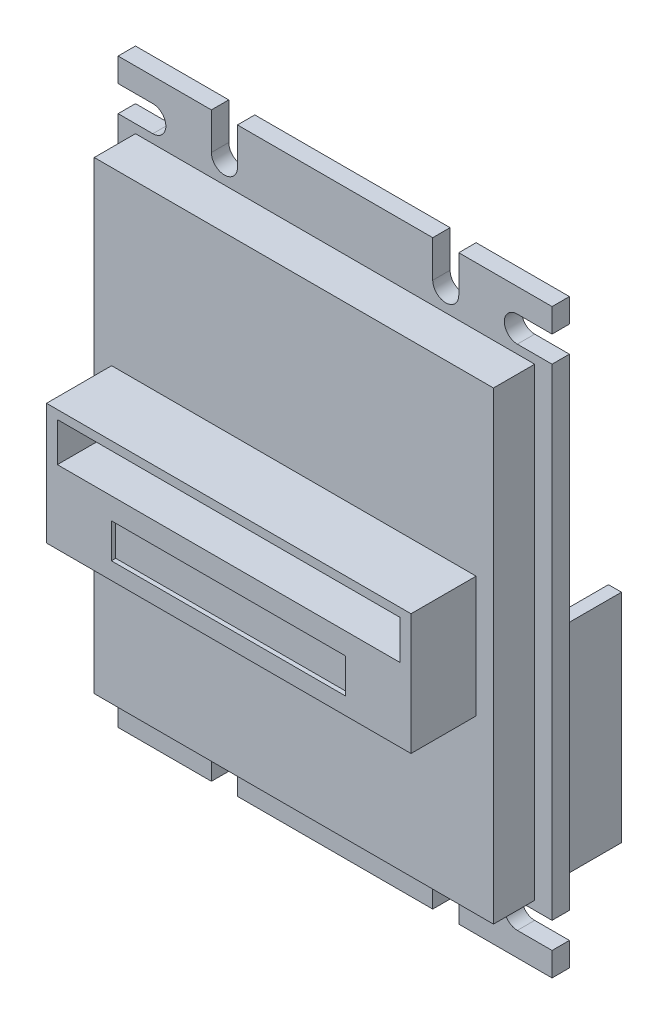
SolidWorks part; units mm, degrees
ref_plane "Front Plane" through (0, 0, 0) normal (0, 0, 1) x (1, 0, 0)
ref_plane "Top Plane" through (0, 0, 0) normal (0, 1, 0) x (1, 0, 0)
ref_plane "Right Plane" through (0, 0, 0) normal (1, 0, 0) x (0, 0, -1)
sketch "Sketch1" plane through (0, 0, 0) normal (0, 0, 1) x (1, 0, 0)
  line L0 (25.5, 0) -> (-25.5, 0) construction
  line L5 (-25.5, 67) -> (-25.5, -67) construction
  line L6 (25.5, 67) -> (25.5, -67) construction
  line L7 (0, -58.5) -> (0, 58.5) construction
  line L8 (25.5, 58.5) -> (-25.5, 58.5) construction
  line L9 (25.5, -58.5) -> (-25.5, -58.5) construction
  line L10 (25.5, 58.5) -> (50, 58.5) construction
  line L11 (-25.5, 58.5) -> (-50, 58.5) construction
  line L12 (50, -58.5) -> (25.5, -58.5) construction
  line L13 (-25.5, -58.5) -> (-50, -58.5) construction
  line L14 (22.5, 58.5) -> (22.5, 67)
  line L15 (28.5, 58.5) -> (28.5, 67)
  line L16 (-28.5, 58.5) -> (-28.5, 67)
  line L17 (-22.5, 58.5) -> (-22.5, 67)
  line L18 (22.5, -58.5) -> (22.5, -67)
  line L19 (28.5, -58.5) -> (28.5, -67)
  line L20 (-28.5, -58.5) -> (-28.5, -67)
  line L21 (-22.5, -58.5) -> (-22.5, -67)
  line L22 (-42, 27.0148) -> (42, 27.0148) construction
  line L23 (-42, 67) -> (-42, -67) construction
  line L24 (42, 67) -> (42, -67) construction
  line L25 (-42, 61.5) -> (-50, 61.5)
  line L26 (-42, 55.5) -> (-50, 55.5)
  line L27 (42, 61.5) -> (50, 61.5)
  line L28 (42, 55.5) -> (50, 55.5)
  line L29 (-42, -55.5) -> (-50, -55.5)
  line L30 (-42, -61.5) -> (-50, -61.5)
  line L31 (42, -55.5) -> (50, -55.5)
  line L32 (42, -61.5) -> (50, -61.5)
  line L33 (-50, 67) -> (-28.5, 67)
  line L34 (-22.5, 67) -> (22.5, 67)
  line L35 (28.5, 67) -> (50, 67)
  line L36 (-50, -67) -> (-28.5, -67)
  line L37 (-22.5, -67) -> (22.5, -67)
  line L38 (28.5, -67) -> (50, -67)
  line L39 (-50, 67) -> (-50, 61.5)
  line L40 (-50, 55.5) -> (-50, -55.5)
  line L41 (-50, -61.5) -> (-50, -67)
  line L42 (50, 67) -> (50, 61.5)
  line L43 (50, 55.5) -> (50, -55.5)
  line L44 (50, -61.5) -> (50, -67)
  arc A0 (28.5, 58.5) -> (22.5, 58.5) centre (25.5, 58.5) cw
  arc A1 (-22.5, 58.5) -> (-28.5, 58.5) centre (-25.5, 58.5) cw
  arc A2 (22.5, -58.5) -> (28.5, -58.5) centre (25.5, -58.5) cw
  arc A3 (-28.5, -58.5) -> (-22.5, -58.5) centre (-25.5, -58.5) cw
  arc A4 (-42, 61.5) -> (-42, 55.5) centre (-42, 58.5) cw
  arc A5 (42, 61.5) -> (42, 55.5) centre (42, 58.5) ccw
  arc A6 (-42, -55.5) -> (-42, -61.5) centre (-42, -58.5) cw
  arc A7 (42, -61.5) -> (42, -55.5) centre (42, -58.5) cw
  point P0 (0, 0)
  point P7 (0, 0)
  point P14 (0, 0)
  point P41 (0, 27.0148)
  dimension "D5" = 84
  dimension "D1" = 134
  dimension "D2" = 100
  dimension "D3" = 51
  dimension "D4" = 117
extrude "Boss-Extrude1" add sketch "Sketch1" along normal blind 4
sketch "Sketch2" plane through (0, 0, 0) normal (0, 0, 1) x (1, 0, 0)
  line L1 (-46, 53.5) -> (46, 53.5)
  line L2 (-46, 53.5) -> (-46, -53.5)
  line L3 (-46, -53.5) -> (46, -53.5)
  line L4 (46, 53.5) -> (46, -53.5)
  line L5 (0, -53.5) -> (0, 53.5) construction
  line L6 (-46, 0) -> (46, 0) construction
  point P0 (0, 0)
  dimension "D1" = 92
  dimension "D2" = 107
extrude "Boss-Extrude2" add sketch "Sketch2" along normal blind 13.5
sketch "Sketch3" plane through (0, 0, 13.5) normal (0, 0, 1) x (1, 0, 0)
  line L1 (-42, 13.95) -> (42, 13.95)
  line L2 (-42, 13.95) -> (-42, -13.95)
  line L3 (-42, -13.95) -> (42, -13.95)
  line L4 (42, 13.95) -> (42, -13.95)
  line L5 (0, -13.95) -> (0, 13.95) construction
  line L6 (-42, 0) -> (42, 0) construction
  point P0 (0, 0)
  dimension "D1" = 27.9
  dimension "D2" = 84
extrude "Boss-Extrude3" add sketch "Sketch3" along normal blind 15
sketch "Sketch4" plane through (0, 0, 28.5) normal (0, 0, 1) x (1, 0, 0)
  line L0 (0, 13.95) -> (0, 11.95) construction
  line L1 (42, 13.95) -> (-42, 13.95) construction
  line L2 (0, 11.95) -> (0, 7.45) construction
  line L4 (39.5, 2.95) -> (-39.5, 2.95)
  line L5 (39.5, 2.95) -> (39.5, 11.95)
  line L6 (39.5, 11.95) -> (-39.5, 11.95)
  line L7 (-39.5, 2.95) -> (-39.5, 11.95)
  line L8 (0, 11.95) -> (0, 2.95) construction
  line L9 (39.5, 7.45) -> (-39.5, 7.45) construction
  dimension "D1" = 2
  dimension "D2" = 4.5
  dimension "D3" = 79
  dimension "D4" = 9
extrude "Cut-Extrude1" cut sketch "Sketch4" against normal through all
sketch "Sketch5" plane through (0, 0, 28.5) normal (0, 0, 1) x (1, 0, 0)
  line L1 (-27.0517, -2.0191) -> (26.9483, -2.0191)
  line L2 (-27.0517, -2.0191) -> (-27.0517, -10.0191)
  line L3 (-27.0517, -10.0191) -> (26.9483, -10.0191)
  line L4 (26.9483, -2.0191) -> (26.9483, -10.0191)
  line L5 (-0.0517, -10.0191) -> (-0.0517, -2.0191) construction
  line L6 (-27.0517, -6.0191) -> (26.9483, -6.0191) construction
  point P0 (-0.0517, -6.0191)
  dimension "D1" = 8
  dimension "D2" = 54
extrude "Cut-Extrude2" cut sketch "Sketch5" against normal blind 1
sketch "Sketch6" plane through (0, 0, 0) normal (0, 0, -1) x (-1, 0, 0)
  line L0 (0, -67) -> (0, -53) construction
  line L1 (22.5, -67) -> (-22.5, -67) construction
  line L2 (-45, -53) -> (45, -53)
  line L3 (-45, -53) -> (-45, -3)
  line L4 (45, -53) -> (45, -3)
  line L5 (45, -3) -> (42, -3)
  line L6 (-45, -3) -> (-42, -3)
  line L7 (0, -53) -> (0, -50) construction
  line L8 (-42, -3) -> (-42, -50)
  line L9 (-42, -50) -> (42, -50)
  line L10 (42, -50) -> (42, -3)
  point P7 (0, -53)
  dimension "D1" = 14
  dimension "D2" = 90
  dimension "D3" = 50
  dimension "D4" = 3
  dimension "D5" = 3
  dimension "D6" = 3
extrude "Boss-Extrude4" add sketch "Sketch6" along normal blind 17
